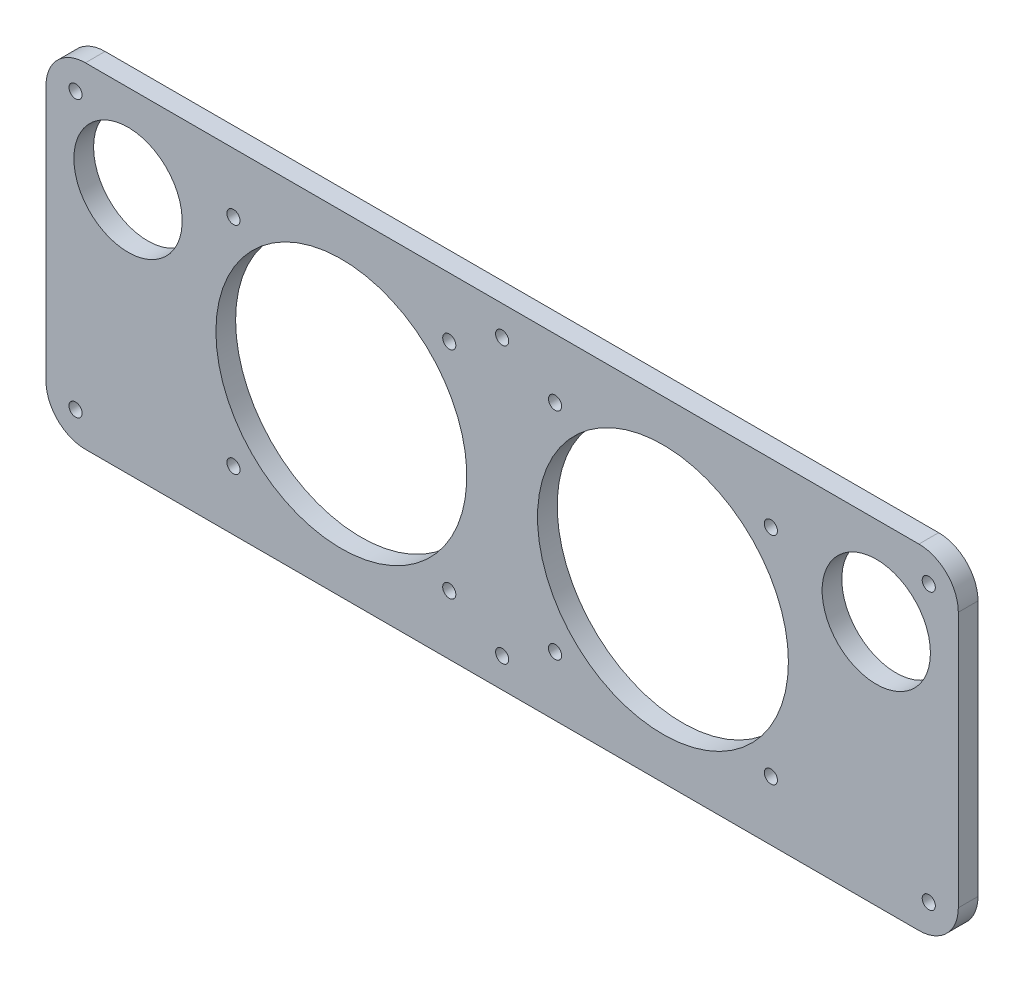
SolidWorks part; units mm, degrees
material "ABS"
ref_plane "Front Plane" through (0, 0, 0) normal (0, 0, 1) x (1, 0, 0)
ref_plane "Top Plane" through (0, 0, 0) normal (0, 1, 0) x (1, 0, 0)
ref_plane "Right Plane" through (0, 0, 0) normal (1, 0, 0) x (0, 0, -1)
sketch "Sketch1" plane through (0, 0, 0) normal (0, 0, 1) x (1, 0, 0)
  line L0 (-3, 0) -> (0, 0) construction
  line L1 (-3, 51) -> (139, 51)
  line L2 (-3, 51) -> (-3, -51)
  line L3 (-3, -51) -> (139, -51)
  line L4 (139, 51) -> (139, -51)
  dimension "D1" = 142
  dimension "D2" = 102
  dimension "D3" = 3
extrude "Boss-Extrude1" add sketch "Sketch1" against normal blind 6
sketch "Sketch2" plane through (0, 0, 0) normal (0, 0, 1) x (1, 0, 0)
  circle A0 centre (49, 0) radius 38.227
  dimension "D1" = 76.454
  dimension "D2" = 49
extrude "Cut-Extrude1" cut sketch "Sketch2" against normal through all
sketch "Sketch4" plane through (0, 0, 0) normal (0, 0, 1) x (1, 0, 0)
  line L0 (49, 0) -> (49, 51) construction
  line L2 (81.8805, 32.8805) -> (49, 0) construction
  line L3 (139, 51) -> (-3, 51) construction
  circle A0 centre (81.8805, 32.8805) radius 2
  dimension "D1" = 4
  dimension "D2" = 46.5
  dimension "D3" = 45
extrude "Cut-Extrude2" cut sketch "Sketch4" against normal through all
pattern_circular "CirPattern1" count 4 over 360 about axis through (49, 0, 0) along (0, 0, 1) of "Cut-Extrude2"
sketch "Sketch5" plane through (0, 0, 0) normal (0, 0, 1) x (1, 0, 0)
  circle A0 centre (114, 24) radius 16.5
  circle A1 centre (49, 0) radius 38.227 construction
  dimension "D1" = 33
  dimension "D3" = 24
  dimension "D2" = 65
extrude "Cut-Extrude3" cut sketch "Sketch5" against normal through all
sketch "Sketch6" plane through (0, 0, 0) normal (0, 0, 1) x (1, 0, 0)
  circle A0 centre (117, -23) radius 17.465
  circle A1 centre (49, 0) radius 38.227 construction
  dimension "D1" = 34.93
  dimension "D2" = 68
  dimension "D3" = 23
extrude "Cut-Extrude4" [suppressed] cut sketch "Sketch6" against normal through all
mirror "Mirror2" about plane through (0, 0, 0) normal (1, 0, 0) of bodies 107
fillet "Fillet1" radius 12 4 edges at (-139, 51, -3) (-139, -51, -3) (139, -51, -3) (139, 51, -3)
hole_wizard "Ø5.0 (5) Diameter Hole1" positions "Sketch9" profile "Sketch10" hole size "Ø5.0" standard "ANSI Metric" end condition through all
sketch "Sketch9" plane through (0, 0, 0) normal (0, 0, 1) x (1, 0, 0)
  line L1 (-130, 42) -> (130, 42)
  line L2 (-130, 42) -> (-130, -42)
  line L3 (-130, -42) -> (130, -42)
  line L4 (130, 42) -> (130, -42)
  line L5 (-130, 42) -> (130, -42) construction
  line L6 (0, 42) -> (0, -42) construction
  point P0 (-130, 42)
  point P1 (130, -42)
  point P4 (-130, -42)
  point P5 (130, 42)
  point P87 (0, 42)
  point P88 (0, -42)
  dimension "D1" = 260
  dimension "D2" = 84
  dimension "D3" = 84
sketch "Sketch10" plane through (-130, 42, 0) normal (1, 0, 0) x (0, -1, 0)
  line L0 (0, 0) -> (0, 6)
  line L1 (0, 6) -> (2, 6)
  line L2 (2, 6) -> (2, 0)
  line L5 (2, 0) -> (0, 0)
  line L11 (0, -6.35) -> (0, 107.95) construction
  dimension "Thru Hole Dia." = 4
  dimension "Thru Hole Depth" = 6
chamfer "Chamfer1" [suppressed] distance 2 angle 45
equation "\"t\" = 6mm"
equation "\"D1@Sketch1\"=\"t\"*2+\"width\""
equation "\"D2@Sketch1\"=\"t\"*2+\"height\""
equation "\"D1@Boss-Extrude1\"=\"t\""
equation "\"D3@Sketch1\"=\"t\"/2"
equation "\"width\" = 13cm"
equation "\"height\" = 9cm"
equation "\"depth\" = 7.5cm"
equation "\"D1@Sketch9\"=\"width\"*2 + \"t\"-6"
equation "\"D2@Sketch9\"=\"height\"-6"
equation "\"D3@Sketch9\"=\"height\"-6"
equation "\"D1@Sketch7\"=\"width\"*2 + \"t\""
